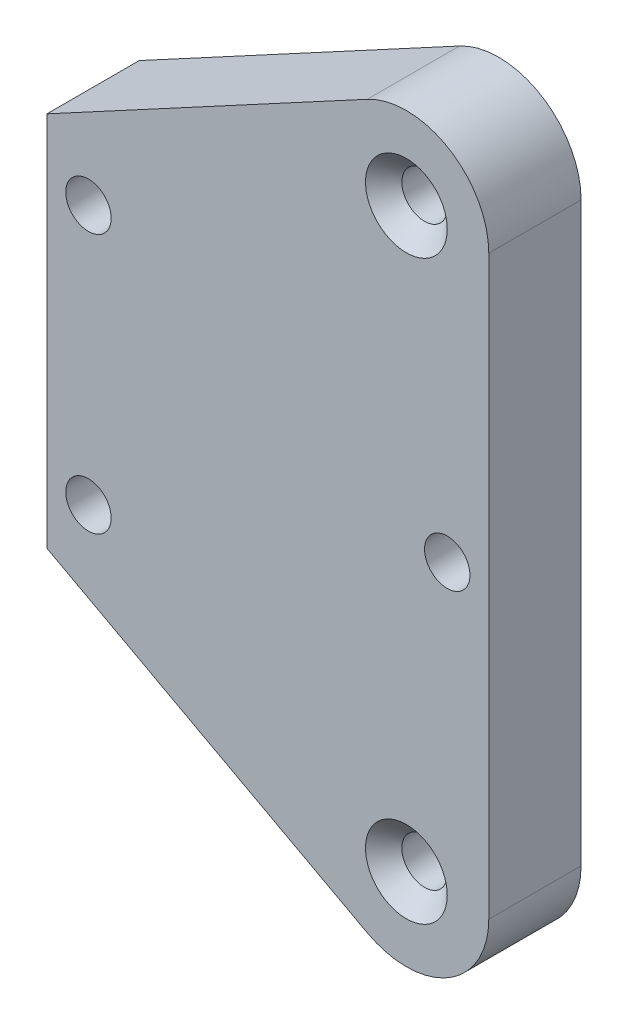
SolidWorks part; units mm, degrees
ref_plane "Front Plane" through (0, 0, 0) normal (0, 0, 1) x (1, 0, 0)
ref_plane "Top Plane" through (0, 0, 0) normal (0, 1, 0) x (1, 0, 0)
ref_plane "Right Plane" through (0, 0, 0) normal (1, 0, 0) x (0, 0, -1)
sketch "Sketch1" plane through (0, 0, 0) normal (0, 0, 1) x (1, 0, 0)
  line L0 (0, 22.225) -> (0, -22.225) construction
  line L1 (-27.7, 14.5) -> (2.3, 14.5) construction
  line L2 (-27.7, 14.5) -> (-27.7, -14.5)
  line L3 (-27.7, -14.5) -> (2.3, -14.5) construction
  line L4 (2.3, 14.5) -> (2.3, -14.5) construction
  line L5 (-27.7, 14.5) -> (2.3, -14.5) construction
  line L6 (-27.7, -14.5) -> (2.3, 14.5) construction
  line L7 (6.35, 22.225) -> (6.35, -22.225) construction
  line L8 (-6.35, 22.225) -> (-6.35, -22.225) construction
  line L9 (-27.7, 14.5) -> (-3.0143, 27.8139)
  line L10 (-27.7, -14.5) -> (-3.0143, -27.8139)
  line L11 (6.35, 22.225) -> (6.35, -22.225)
  line L12 (-24.5, 10) -> (-24.5, -10) construction
  arc A0 (6.35, 22.225) -> (-6.35, 22.225) centre (0, 22.225) ccw construction
  arc A1 (-6.35, -22.225) -> (6.35, -22.225) centre (0, -22.225) ccw construction
  circle A2 centre (0, 22.225) radius 1.75
  circle A3 centre (0, -22.225) radius 1.75
  arc A4 (-3.0143, 27.8139) -> (6.35, 22.225) centre (0, 22.225) cw
  arc A5 (-3.0143, -27.8139) -> (6.35, -22.225) centre (0, -22.225) ccw
  circle A6 centre (-24.5, 10) radius 1.75
  circle A7 centre (-24.5, -10) radius 1.75
  circle A8 centre (3.15, 0) radius 1.75
  point P0 (-12.7, 0)
  point P7 (0, 0)
  point P29 (-24.5, 0)
  point P30 (0, 0)
  point P31 (-21.5599, -10)
  dimension "D4" = 3.5
  dimension "D6" = 6.35
  dimension "D10" = 3.5
  dimension "D1" = 30
  dimension "D2" = 29
  dimension "D3" = 12.7
  dimension "D5" = 44.45
  dimension "D7" = 3.2
  dimension "D8" = 3.2
  dimension "D9" = 20
extrude "Boss-Extrude1" add sketch "Sketch1" along normal blind 7.112
hole_wizard "CSK for M3 Flat Head Machine Screw1" positions "3DSketch1" profile "Sketch4" countersink size "M3" standard "ANSI Metric" end condition through all
sketch3d "3DSketch1"
  line L0 (-24.5, 10, 7.112) -> (-24.5, 10, 0) construction
  line L1 (-24.5, -10, 7.112) -> (-24.5, -10, 0) construction
  point P0 (-24.5, 10, 0)
  point P4 (-24.5, -10, 0)
sketch "Sketch4" plane through (-24.5, 10, 0) normal (1, 0, 0) x (0, 1, 0)
  line L0 (0, 0) -> (0, 7.112)
  line L1 (0, 7.112) -> (1.6, 7.112)
  line L2 (1.6, 7.112) -> (1.6, 1.55)
  line L3 (1.6, 1.55) -> (3.15, 0)
  line L5 (3.15, 0) -> (0, 0)
  line L6 (-1.6, 1.55) -> (-3.15, 0) construction
  line L11 (0, -6.35) -> (0, 107.95) construction
  dimension "Thru Hole Dia." = 3.2
  dimension "Thru Hole Depth" = 7.112
  dimension "Near C'Sink Dia." = 6.3
  dimension "Near C'Sink Angle" = 90
hole_wizard "CSK for M3 Flat Head Machine Screw2" positions "Sketch5" profile "Sketch6" countersink size "M3" standard "ANSI Metric" end condition through all
sketch "Sketch5" plane through (0, 0, 0) normal (0, 0, -1) x (-1, 0, 0)
  point P0 (-3.15, 0)
sketch "Sketch6" plane through (3.15, 0, 0) normal (1, 0, 0) x (0, 1, 0)
  line L0 (0, 0) -> (0, 7.112)
  line L1 (0, 7.112) -> (1.6, 7.112)
  line L2 (1.6, 7.112) -> (1.6, 1.55)
  line L3 (1.6, 1.55) -> (3.15, 0)
  line L5 (3.15, 0) -> (0, 0)
  line L6 (-1.6, 1.55) -> (-3.15, 0) construction
  line L11 (0, -6.35) -> (0, 107.95) construction
  dimension "Thru Hole Dia." = 3.2
  dimension "Thru Hole Depth" = 7.112
  dimension "Near C'Sink Dia." = 6.3
  dimension "Near C'Sink Angle" = 90
hole_wizard "CSK for M3 Flat Head Machine Screw3" positions "Sketch7" profile "Sketch8" countersink size "M3" standard "ANSI Metric" end condition through all
sketch "Sketch7" plane through (0, 0, 7.112) normal (0, 0, 1) x (1, 0, 0)
  point P0 (0, 22.225)
  point P3 (0, -22.225)
sketch "Sketch8" plane through (0, 22.225, 7.112) normal (1, 0, 0) x (0, -1, 0)
  line L0 (0, 0) -> (0, 7.112)
  line L1 (0, 7.112) -> (1.6, 7.112)
  line L2 (1.6, 7.112) -> (1.6, 1.55)
  line L3 (1.6, 1.55) -> (3.15, 0)
  line L5 (3.15, 0) -> (0, 0)
  line L6 (-1.6, 1.55) -> (-3.15, 0) construction
  line L11 (0, -6.35) -> (0, 107.95) construction
  dimension "Thru Hole Dia." = 3.2
  dimension "Thru Hole Depth" = 7.112
  dimension "Near C'Sink Dia." = 6.3
  dimension "Near C'Sink Angle" = 90
